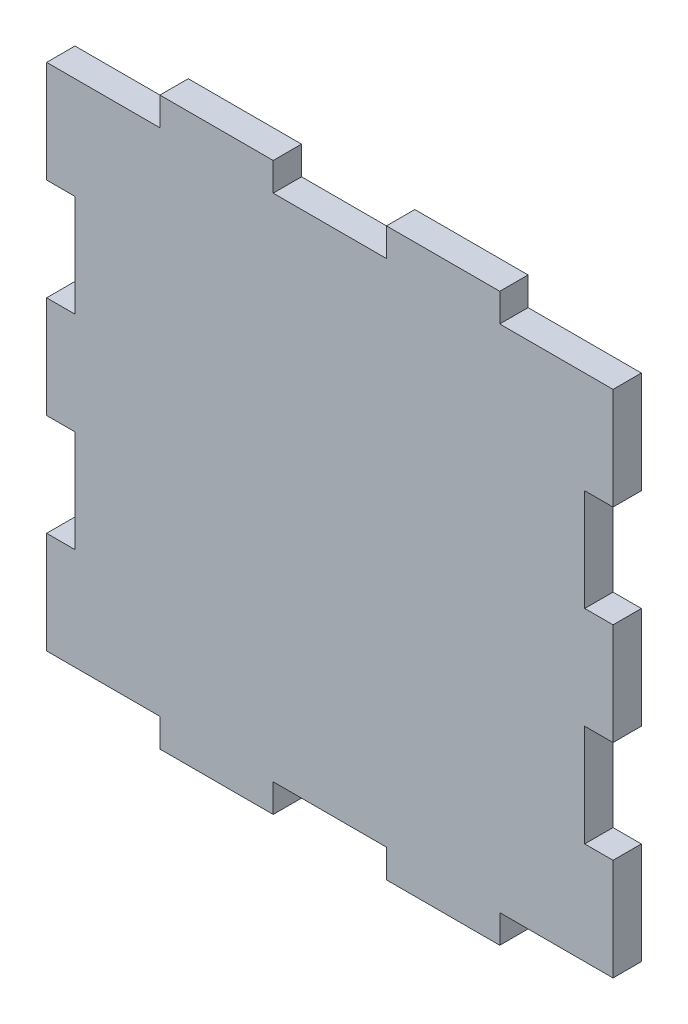
SolidWorks part; units mm, degrees
ref_plane "Front Plane" through (0, 0, 0) normal (0, 0, 1) x (1, 0, 0)
ref_plane "Top Plane" through (0, 0, 0) normal (0, 1, 0) x (1, 0, 0)
ref_plane "Right Plane" through (0, 0, 0) normal (1, 0, 0) x (0, 0, -1)
sketch "Esquisse1" plane through (0, 0, 0) normal (0, 0, 1) x (1, 0, 0)
  line L1 (0, 0) -> (-100, 0)
  line L2 (0, 0) -> (0, -90)
  line L3 (0, -90) -> (-100, -90)
  line L4 (-100, 0) -> (-100, -90)
  line L5 (-50, -90) -> (-50, 0) construction
  line L6 (0, -45) -> (-100, -45) construction
  point P72 (-50, -45)
  dimension "D1" = 100
  dimension "D2" = 90
extrude "Boss.-Extru.1" add sketch "Esquisse1" along normal blind 5
sketch "Esquisse2" plane through (0, 0, 5) normal (0, 0, 1) x (1, 0, 0)
  line L1 (0, 0) -> (-100, 0) construction
  line L10 (-100, 0) -> (-100, -18)
  line L11 (-100, 0) -> (-100, -90) construction
  line L12 (-100, -18) -> (-95, -18)
  line L13 (-95, -18) -> (-95, -36)
  line L14 (-95, -36) -> (-100, -36)
  line L15 (-100, -36) -> (-100, -54)
  line L16 (-100, -54) -> (-95, -54)
  line L17 (-95, -54) -> (-95, -72)
  line L18 (-95, -72) -> (-100, -72)
  line L19 (-100, -72) -> (-100, -90)
  line L30 (-100, 0) -> (0, 0)
  line L31 (0, 0) -> (0, -18)
  line L32 (0, -90) -> (0, 0) construction
  line L33 (0, -18) -> (-5, -18)
  line L34 (-5, -18) -> (-5, -36)
  line L35 (-5, -36) -> (0, -36)
  line L36 (0, -36) -> (0, -54)
  line L37 (0, -54) -> (-5, -54)
  line L38 (-5, -54) -> (-5, -72)
  line L39 (-5, -72) -> (0, -72)
  line L40 (0, -72) -> (0, -90)
  line L41 (0, -90) -> (-100, -90)
  dimension "D7" = 18
  dimension "D8" = 5
  dimension "D9" = 18
  dimension "D16" = 5
  dimension "D17" = 18
  dimension "D18" = 18
  dimension "D19" = 18
  dimension "D20" = 18
  dimension "D21" = 5
extrude "Enlèv. mat.-Extru.1" cut sketch "Esquisse2" against normal blind 5 flip side to cut
sketch "Esquisse3" plane through (0, 0, 5) normal (0, 0, 1) x (1, 0, 0)
  line L0 (-100, 0) -> (-80, 0)
  line L1 (0, 0) -> (-100, 0) construction
  line L2 (-80, 0) -> (-80, 5)
  line L3 (0, 5) -> (-20, 5) construction
  line L4 (-80, 5) -> (-60, 5)
  line L5 (-60, 5) -> (-60, 0)
  line L6 (-60, 0) -> (-40, 0)
  line L7 (-40, 0) -> (-40, 5)
  line L8 (-40, 5) -> (-20, 5)
  line L9 (-20, 5) -> (-20, 0)
  line L10 (-20, 0) -> (0, 0)
  line L11 (-80, 0) -> (-60, 0)
  line L12 (-40, 0) -> (-20, 0)
  line L13 (-100, -45) -> (0, -45) construction
  line L14 (-100, -36) -> (-100, -54) construction
  line L15 (0, -54) -> (0, -36) construction
  line L16 (-40, -90) -> (-20, -90)
  line L17 (-80, -90) -> (-60, -90)
  line L18 (-20, -90) -> (0, -90)
  line L19 (-20, -95) -> (-20, -90)
  line L20 (-40, -95) -> (-20, -95)
  line L21 (-40, -90) -> (-40, -95)
  line L22 (-60, -90) -> (-40, -90)
  line L23 (-60, -95) -> (-60, -90)
  line L24 (-80, -95) -> (-60, -95)
  line L25 (-80, -90) -> (-80, -95)
  line L26 (-100, -90) -> (-80, -90)
  line M8 (0, 0) -> (-100, 0)
  line M18 (-100, -90) -> (0, -90)
  dimension "D1" = 20
  dimension "D2" = 20
extrude "Boss.-Extru.2" add sketch "Esquisse3" against normal blind 5 contours L5 L4 L2 M8 | L9 L8 L7 M8 | L25 L24 L23 M18 | L21 L20 L19 M18
